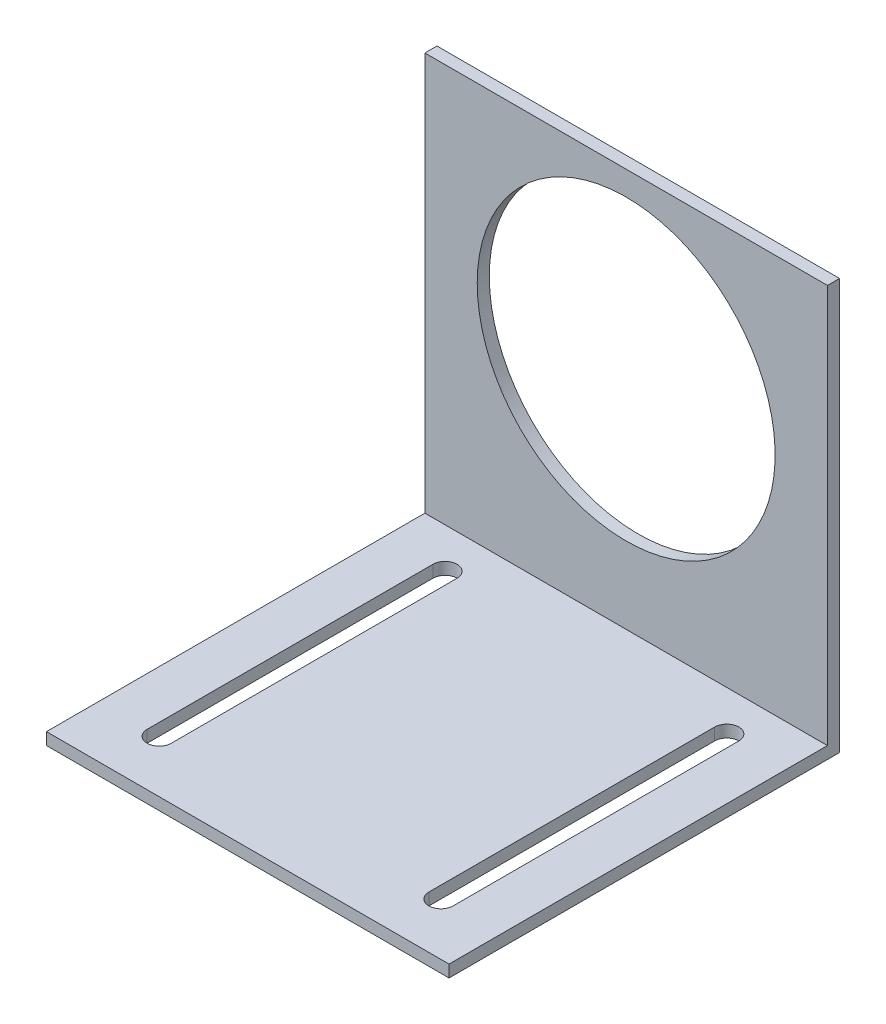
SolidWorks part; units mm, degrees
material "Plain Carbon Steel"
ref_plane "Front Plane" through (0, 0, 0) normal (0, 0, 1) x (1, 0, 0)
ref_plane "Top Plane" through (0, 0, 0) normal (0, 1, 0) x (1, 0, 0)
ref_plane "Right Plane" through (0, 0, 0) normal (1, 0, 0) x (0, 0, -1)
sketch "Sketch1" plane through (0, 0, 0) normal (0, 1, 0) x (1, 0, 0)
  line L0 (15, 84) -> (15, 13) construction
  line L1 (0, 0) -> (100, 0)
  line L2 (0, 0) -> (0, 97)
  line L3 (0, 97) -> (100, 97)
  line L4 (100, 0) -> (100, 97)
  line L5 (18, 84) -> (18, 13)
  line L6 (12, 84) -> (12, 13)
  line L7 (85, 13) -> (85, 84) construction
  line L8 (82, 13) -> (82, 84)
  line L9 (88, 13) -> (88, 84)
  arc A0 (18, 84) -> (12, 84) centre (15, 84) ccw
  arc A1 (12, 13) -> (18, 13) centre (15, 13) ccw
  arc A2 (82, 13) -> (88, 13) centre (85, 13) ccw
  arc A3 (88, 84) -> (82, 84) centre (85, 84) ccw
  point P7 (15, 48.5)
  point P13 (85, 48.5)
  point P20 (100, 48.5)
  point P22 (0, 48.5)
  dimension "D1" = 100
  dimension "D2" = 97
  dimension "D3" = 12
  dimension "D4" = 10
  dimension "D5" = 6
  dimension "D6" = 12
  dimension "D7" = 10
  dimension "D8" = 6
extrude "Boss-Extrude1" add sketch "Sketch1" along normal blind 3
sketch "Sketch2" plane through (0, 0, -97) normal (0, 0, -1) x (-1, 0, 0)
  line L0 (-100, 3) -> (-100, 0) construction
  line L1 (0, 0) -> (-100, 0)
  line L2 (0, 0) -> (0, 102)
  line L3 (0, 102) -> (-100, 102)
  line L4 (-100, 0) -> (-100, 102)
  circle A0 centre (-50, 59) radius 37
  dimension "D2" = 74
  dimension "D1" = 102
  dimension "D3" = 6
  dimension "D4" = 13
extrude "Boss-Extrude2" add sketch "Sketch2" against normal blind 3
